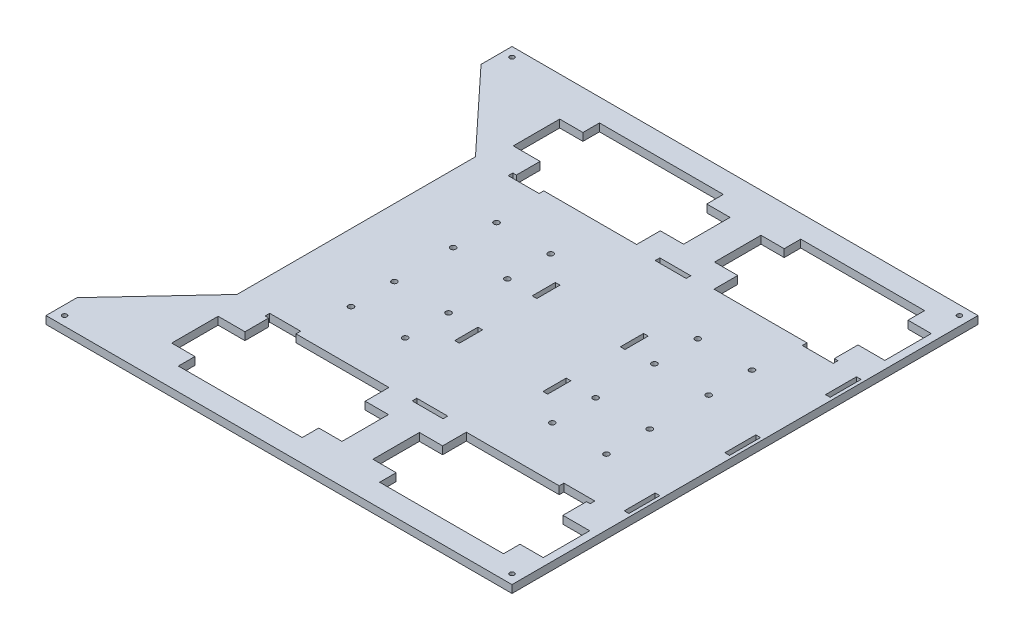
SolidWorks part; units mm, degrees
ref_plane "Front Plane" through (0, 0, 0) normal (0, 0, 1) x (1, 0, 0)
ref_plane "Top Plane" through (0, 0, 0) normal (0, 1, 0) x (1, 0, 0)
ref_plane "Right Plane" through (0, 0, 0) normal (1, 0, 0) x (0, 0, -1)
sketch "Sketch1" plane through (0, 0, 0) normal (0, 1, 0) x (1, 0, 0)
  line L0 (25, 147.6878) -> (25, -153.3122) construction
  line L1 (-151, 147.6878) -> (150, 147.6878)
  line L2 (-151, 147.6878) -> (-151, 127.6878)
  line L3 (-151, -153.3122) -> (150, -153.3122)
  line L4 (150, 147.6878) -> (150, -153.3122)
  line L5 (-150, -2.8122) -> (150, -2.8122) construction
  line L6 (-151, 77.1878) -> (-81.1104, 77.1878) construction
  line L7 (-151, -82.8122) -> (-3, -82.8122) construction
  line L8 (72.5, 44.1878) -> (72.5, 16.1878) construction
  line L25 (107.5, 44.1878) -> (107.5, 16.1878) construction
  line L26 (107.5, 16.1878) -> (72.5, 16.1878) construction
  line L27 (107.5, 44.1878) -> (72.5, 44.1878) construction
  line L28 (-22.5, -49.8122) -> (-22.5, -21.8122) construction
  line L29 (-57.5, -49.8122) -> (-57.5, -21.8122) construction
  line L30 (-57.5, -21.8122) -> (-22.5, -21.8122) construction
  line L31 (-57.5, -49.8122) -> (-22.5, -49.8122) construction
  line L32 (-57.5, 44.1878) -> (-22.5, 44.1878) construction
  line L33 (-57.5, 16.1878) -> (-22.5, 16.1878) construction
  line L34 (-57.5, 44.1878) -> (-57.5, 16.1878) construction
  line L35 (107.5, -49.8122) -> (72.5, -49.8122) construction
  line L36 (-22.5, 44.1878) -> (-22.5, 16.1878) construction
  line L37 (107.5, -21.8122) -> (72.5, -21.8122) construction
  line L38 (107.5, -49.8122) -> (107.5, -21.8122) construction
  line L39 (72.5, -49.8122) -> (72.5, -21.8122) construction
  line L40 (-179.4189, 127.6878) -> (-151, 127.6878) construction
  line L41 (-151, -133.3122) -> (-151, -153.3122)
  line L42 (-193.6528, -133.3122) -> (-151, -133.3122) construction
  line L43 (-101, -184.1209) -> (-101, -153.3122) construction
  line L44 (107.5, -49.8122) -> (150, -49.8122) construction
  line L45 (-101.1104, -79.8122) -> (-101.1104, 74.1878)
  line L46 (-101.1104, -79.8122) -> (-151, -133.3122)
  line L47 (-101.1104, 74.1878) -> (-151, 127.6878)
  line L48 (-80, 101.8756) -> (130, 101.8756) construction
  line L49 (35, 122.5) -> (35, 92.5)
  line L55 (35, 92.5) -> (50, 92.5)
  line L84 (130, 74.1878) -> (150, 74.1878) construction
  line L85 (-77.6818, 77.1878) -> (-77.6818, 92.5)
  line L86 (-80, 77.1878) -> (-77.6818, 77.1878)
  line L103 (50, 92.5) -> (50, 77.1878)
  line L104 (50, 77.1878) -> (110, 77.1878)
  line L106 (110, 77.1878) -> (110, 74.1878)
  line L107 (110, 74.1878) -> (130, 74.1878)
  line L108 (130, 74.1878) -> (130, 77.1878)
  line L109 (130, 77.1878) -> (127.6818, 77.1878)
  line L110 (127.6818, 77.1878) -> (127.6818, 92.5)
  line L111 (127.6818, 92.5) -> (145, 92.5)
  line L112 (145, 92.5) -> (145, 122.5)
  line L113 (145, 122.5) -> (130, 122.5)
  line L114 (130, 122.5) -> (130, 133.1878)
  line L115 (130, 133.1878) -> (50, 133.1878)
  line L120 (50, 133.1878) -> (50, 122.5)
  line L121 (50, 122.5) -> (35, 122.5)
  line L122 (90, 133.1878) -> (90, 77.1878) construction
  line L123 (-80, 74.1878) -> (-80, 77.1878)
  line L124 (-60, 74.1878) -> (-80, 74.1878)
  line L125 (-60, 77.1878) -> (-60, 74.1878)
  line L126 (0, 77.1878) -> (-60, 77.1878)
  line L127 (0, 92.5) -> (0, 77.1878)
  line L130 (0, 122.5) -> (15, 122.5)
  line L131 (0, 133.1878) -> (0, 122.5)
  line L132 (-80, 133.1878) -> (0, 133.1878)
  line L133 (-80, 122.5) -> (-80, 133.1878)
  line L134 (-95, 122.5) -> (-80, 122.5)
  line L135 (-95, 92.5) -> (-95, 122.5)
  line L136 (-77.6818, 92.5) -> (-95, 92.5)
  line L137 (15, 92.5) -> (0, 92.5)
  line L140 (15, 122.5) -> (15, 92.5)
  line L141 (-151, -82.8122) -> (-81.1104, -82.8122) construction
  line L142 (-60, -82.8122) -> (-60, -79.8122)
  line L143 (-60, -79.8122) -> (-80, -79.8122)
  line L144 (-80, -79.8122) -> (-80, -82.8122)
  line L145 (-101.1104, -79.8122) -> (130, -79.8122) construction
  line L146 (35, -79.8122) -> (35, -82.8122)
  line L147 (15, -82.8122) -> (15, -79.8122)
  line L148 (15, -79.8122) -> (35, -79.8122)
  line L149 (130, -79.8122) -> (130, -82.8122)
  line L150 (110, -79.8122) -> (130, -79.8122)
  line L151 (110, -82.8122) -> (110, -79.8122)
  line L152 (-61.1104, -82.8122) -> (50, -82.8122) construction
  line L153 (-101.1104, 74.1878) -> (130, 74.1878) construction
  line L158 (15, 74.1878) -> (35, 74.1878)
  line L159 (15, 77.1878) -> (15, 74.1878)
  line L160 (35, 77.1878) -> (15, 77.1878)
  line L161 (35, 74.1878) -> (35, 77.1878)
  line L166 (-61.1104, 77.1878) -> (50, 77.1878) construction
  line L167 (130, 77.1878) -> (150, 77.1878) construction
  line L169 (90, -138.8122) -> (90, -82.8122) construction
  line L170 (-80, -107.5) -> (130, -107.5) construction
  line L171 (35, -82.8122) -> (15, -82.8122)
  line L172 (15, -128.1244) -> (15, -98.1244)
  line L173 (15, -98.1244) -> (0, -98.1244)
  line L174 (-77.6818, -98.1244) -> (-95, -98.1244)
  line L175 (-95, -98.1244) -> (-95, -128.1244)
  line L176 (-95, -128.1244) -> (-80, -128.1244)
  line L177 (-80, -128.1244) -> (-80, -138.8122)
  line L178 (-80, -138.8122) -> (0, -138.8122)
  line L179 (0, -138.8122) -> (0, -128.1244)
  line L180 (0, -128.1244) -> (15, -128.1244)
  line L181 (0, -98.1244) -> (0, -82.8122)
  line L182 (0, -82.8122) -> (-60, -82.8122)
  line L185 (53, -82.8122) -> (150, -82.8122) construction
  line L186 (-114.6517, -79.8122) -> (-93.3908, -79.8122) construction
  line L187 (-2, 29.6878) -> (-2, 14.6878)
  line L188 (-5, 29.6878) -> (55, 29.6878) construction
  line L189 (-5, 29.6878) -> (-5, 14.6878)
  line L190 (-5, -35.3122) -> (55, -35.3122) construction
  line L192 (-5, 29.6878) -> (55, -35.3122) construction
  line L193 (-5, -35.3122) -> (55, 29.6878) construction
  line L194 (-5, 29.6878) -> (-2, 29.6878)
  line L195 (-5, 14.6878) -> (-2, 14.6878)
  line L196 (-5, -35.3122) -> (-2, -35.3122)
  line L197 (-5, -20.3122) -> (-2, -20.3122)
  line L198 (-5, -20.3122) -> (-5, -35.3122)
  line L199 (-5, 29.6878) -> (-5, -35.3122) construction
  line L200 (-2, -20.3122) -> (-2, -35.3122)
  line L201 (-2, 29.6878) -> (-2, -35.3122) construction
  line L202 (52, -20.3122) -> (52, -35.3122)
  line L203 (55, -20.3122) -> (55, -35.3122)
  line L204 (55, -20.3122) -> (52, -20.3122)
  line L205 (55, -35.3122) -> (52, -35.3122)
  line L206 (55, 14.6878) -> (52, 14.6878)
  line L207 (55, 29.6878) -> (52, 29.6878)
  line L208 (55, 29.6878) -> (55, 14.6878)
  line L209 (52, 29.6878) -> (52, 14.6878)
  line L210 (148, 74.1878) -> (148, 54.1878)
  line L211 (145, 74.1878) -> (145, 54.1878)
  line L212 (145, 74.1878) -> (148, 74.1878)
  line L213 (145, 54.1878) -> (148, 54.1878)
  line L214 (145, 9.1878) -> (148, 9.1878)
  line L215 (145, -10.8122) -> (148, -10.8122)
  line L216 (145, -55.8122) -> (148, -55.8122)
  line L217 (145, -75.8122) -> (148, -75.8122)
  line L218 (145, 74.1878) -> (145, -82.8122) construction
  line L219 (148, 74.1878) -> (148, -82.8122) construction
  line L220 (145, -55.8122) -> (145, -75.8122)
  line L221 (148, -55.8122) -> (148, -75.8122)
  line L222 (145, 9.1878) -> (145, -10.8122)
  line L223 (148, 9.1878) -> (148, -10.8122)
  line L224 (50, -128.1244) -> (35, -128.1244)
  line L225 (50, -138.8122) -> (50, -128.1244)
  line L226 (130, -138.8122) -> (50, -138.8122)
  line L227 (130, -128.1244) -> (130, -138.8122)
  line L228 (145, -128.1244) -> (130, -128.1244)
  line L229 (145, -98.1244) -> (145, -128.1244)
  line L230 (127.6818, -98.1244) -> (145, -98.1244)
  line L231 (127.6818, -82.8122) -> (127.6818, -98.1244)
  line L232 (130, -82.8122) -> (127.6818, -82.8122)
  line L233 (50, -82.8122) -> (110, -82.8122)
  line L234 (50, -98.1244) -> (50, -82.8122)
  line L235 (-80, -82.8122) -> (-77.6818, -82.8122)
  line L236 (-77.6818, -82.8122) -> (-77.6818, -98.1244)
  line L237 (35, -98.1244) -> (50, -98.1244)
  line L238 (35, -128.1244) -> (35, -98.1244)
  line L239 (-148.5, -147.3122) -> (150, -147.3122) construction
  line L240 (-145, -142.9394) -> (-145, -149.5739) construction
  line L241 (144, -141.9011) -> (144, -151.2938) construction
  line L242 (144, 147.6878) -> (144, 135.2978) construction
  line L243 (146.497, 141.6878) -> (127.6818, 141.6878) construction
  line L244 (-151, 141.6878) -> (-131.4371, 141.6878) construction
  line L245 (-145, 147.6878) -> (-145, 129.6255) construction
  circle A0 centre (-57.5, 44.1878) radius 1.75
  circle A1 centre (-22.5, 44.1878) radius 1.75
  circle A2 centre (-22.5, 16.1878) radius 1.75
  circle A3 centre (-57.5, 16.1878) radius 1.75
  circle A4 centre (107.5, 16.1878) radius 1.75
  circle A5 centre (72.5, 16.1878) radius 1.75
  circle A6 centre (72.5, 44.1878) radius 1.75
  circle A7 centre (107.5, 44.1878) radius 1.75
  circle A8 centre (107.5, -49.8122) radius 1.75
  circle A9 centre (72.5, -49.8122) radius 1.75
  circle A10 centre (72.5, -21.8122) radius 1.75
  circle A11 centre (107.5, -21.8122) radius 1.75
  circle A12 centre (-57.5, -21.8122) radius 1.75
  circle A13 centre (-22.5, -21.8122) radius 1.75
  circle A14 centre (-22.5, -49.8122) radius 1.75
  circle A15 centre (-57.5, -49.8122) radius 1.75
  circle A17 centre (144, -147.3122) radius 1.5
  circle A18 centre (-145, -147.3122) radius 1.5
  circle A19 centre (144, 141.6878) radius 1.5
  circle A20 centre (-145, 141.6878) radius 1.5
  point P0 (0, 0)
  point P285 (25, -2.8122)
  point P302 (50, 0)
  dimension "D6" = 80
  dimension "D7" = 20
  dimension "D43" = 3
  dimension "D45" = 3
  dimension "D48" = 6
  dimension "D51" = 3
  dimension "D54" = 3
  dimension "D55" = 6
  dimension "D56" = 6
  dimension "D1" = 301
  dimension "D2" = 301
  dimension "D3" = 125
  dimension "D4" = 80
  dimension "D5" = 80
  dimension "D8" = 50
  dimension "D9" = 5
  dimension "D10" = 20
  dimension "D11" = 20
  dimension "D12" = 110
  dimension "D13" = 20
  dimension "D14" = 28
  dimension "D15" = 35
  dimension "D16" = 20
  dimension "D18" = 137
  dimension "D19" = 137
  dimension "D21" = 65
  dimension "D22" = 35
  dimension "D23" = 15
  dimension "D24" = 30
  dimension "D25" = 2
  dimension "D27" = 20
  dimension "D28" = 3
  dimension "D29" = 45
  dimension "D30" = 33
  dimension "D17" = 56
  dimension "D31" = 35
  dimension "D32" = 21.1104
  dimension "D33" = 20
  dimension "D34" = 75
  dimension "D35" = 20
  dimension "D36" = 75
  dimension "D37" = 7
  dimension "D38" = 20
  dimension "D39" = 45
  dimension "D40" = 14.5
  dimension "D41" = 6
  dimension "D42" = 6
  dimension "D44" = 6
  dimension "D46" = 6
  dimension "D47" = 301
  dimension "D49" = 6
  dimension "D50" = 6
  dimension "D52" = 6
  dimension "D53" = 6
  dimension "D20" = 3
  dimension "D26" = 3
extrude "Boss-Extrude1" add sketch "Sketch1" along normal blind 5
